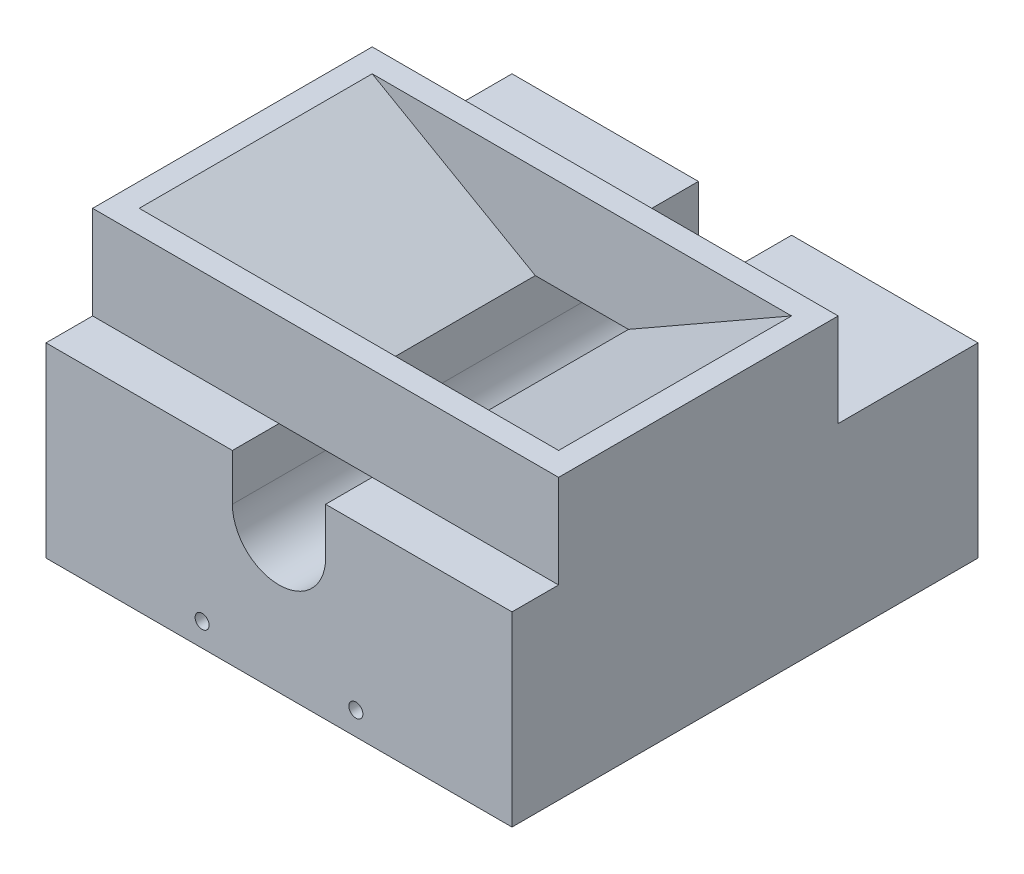
SolidWorks part; units mm, degrees
ref_plane "Front Plane" through (0, 0, 0) normal (0, 0, 1) x (1, 0, 0)
ref_plane "Top Plane" through (0, 0, 0) normal (0, 1, 0) x (1, 0, 0)
ref_plane "Right Plane" through (0, 0, 0) normal (1, 0, 0) x (0, 0, -1)
sketch "Sketch4" plane through (0, 0, 0) normal (0, 0, 1) x (1, 0, 0)
  line L1 (50, -30) -> (-50, -30)
  line L2 (50, -30) -> (50, 30)
  line L3 (50, 30) -> (-50, 30)
  line L4 (-50, -30) -> (-50, 30)
  line L5 (50, -30) -> (-50, 30) construction
  line L6 (50, 30) -> (-50, -30) construction
  point P0 (0, 0)
  dimension "D1" = 60
  dimension "D2" = 100
extrude "Boss-Extrude2" add sketch "Sketch4" along normal blind 100
sketch "Sketch6" plane through (0, 0, 100) normal (0, 0, 1) x (1, 0, 0)
  line L1 (-10, 10) -> (10, 10)
  line L2 (-10, 10) -> (-10, 0)
  line L4 (10, 10) -> (10, 0)
  line L5 (-10, 10) -> (-7.0711, 7.0711) construction
  line L7 (50, -30) -> (50, 30) construction
  arc A0 (-10, 0) -> (10, 0) centre (0, 0) ccw
  point P0 (0, 0)
  dimension "D5" = 20
  dimension "D4" = 40
extrude "Cut-Extrude1" cut sketch "Sketch6" against normal blind 100
sketch "Sketch7" plane through (50, 0, 0) normal (1, 0, 0) x (0, 0, -1)
  line L0 (-100, 30) -> (0, 30) construction
  line L1 (0, 30) -> (-30, 30)
  line L2 (0, 30) -> (0, 10)
  line L3 (0, 10) -> (-30, 10)
  line L4 (-30, 30) -> (-30, 10)
  line L5 (-100, -30) -> (-100, 30) construction
  dimension "D1" = 20
  dimension "D2" = 30
  dimension "D3" = 70
extrude "Cut-Extrude2" cut sketch "Sketch7" against normal blind 100
sketch "Sketch10" plane through (0, 30, 0) normal (0, 1, 0) x (1, 0, 0)
  line L1 (-45, -35) -> (45, -35)
  line L2 (-45, -35) -> (-45, -85)
  line L3 (-45, -85) -> (45, -85)
  line L4 (45, -35) -> (45, -85)
  line L9 (-50, -100) -> (-50, -30) construction
  line L10 (-50, -30) -> (-10, -30) construction
  dimension "D1" = 50
  dimension "D3" = 90
  dimension "D6" = 5
  dimension "D7" = 5
extrude "Cut-Extrude6" cut sketch "Sketch10" against normal blind 20
sketch "Sketch11" plane through (0, 0, 35) normal (0, 0, 1) x (1, 0, 0)
  line L0 (-45, 10) -> (-45, 30) construction
  line L2 (-45, 30) -> (-45, 10)
  line L3 (-45, 10) -> (-10, 10)
  line L5 (45, 30) -> (-45, 30) construction
  line L6 (-45, 30) -> (-10, 10)
extrude "Boss-Extrude3" add sketch "Sketch11" along normal up to next
sketch "Sketch12" plane through (0, 0, 35) normal (0, 0, 1) x (1, 0, 0)
  line L0 (10, 10) -> (45, 30)
  line L1 (10, 10) -> (45, 10)
  line L4 (45, 10) -> (45, 30)
extrude "Boss-Extrude4" add sketch "Sketch12" along normal up to next
sketch "Sketch13" plane through (0, 0, 100) normal (0, 0, 1) x (1, 0, 0)
  line L1 (-50, -30) -> (50, -30) construction
  circle A0 centre (-16.5, -25) radius 1.5
  circle A1 centre (16.5, -25) radius 1.5
  point P9 (0, 0)
  dimension "D1" = 3
  dimension "D2" = 3
  dimension "D3" = 16.5
  dimension "D4" = 16.5
  dimension "D5" = 5
  dimension "D6" = 5
extrude "Cut-Extrude7" cut sketch "Sketch13" against normal blind 40
sketch "Sketch14" plane through (0, -30, 0) normal (0, -1, 0) x (1, 0, 0)
  line L9 (-50, 100) -> (50, 100) construction
  line L10 (-26.5, 95) -> (-6.5, 95)
  line L11 (-26.5, 95) -> (-26.5, 55)
  line L12 (-26.5, 55) -> (-6.5, 55)
  line L13 (-6.5, 95) -> (-6.5, 55)
  line L14 (6.5, 95) -> (26.5, 95)
  line L15 (6.5, 95) -> (6.5, 55)
  line L16 (6.5, 55) -> (26.5, 55)
  line L17 (26.5, 95) -> (26.5, 55)
  line L18 (-50, 100) -> (-50, 0) construction
  line L19 (50, 100) -> (50, 0) construction
  dimension "D1" = 5
  dimension "D2" = 5
  dimension "D3" = 40
  dimension "D4" = 40
  dimension "D5" = 20
  dimension "D6" = 20
  dimension "D7" = 23.5
  dimension "D8" = 23.5
extrude "Cut-Extrude8" cut sketch "Sketch14" against normal blind 10
sketch "Sketch15" plane through (0, 0, 0) normal (0, 0, -1) x (-1, 0, 0)
  line L1 (50, -30) -> (-50, -30) construction
  line L3 (-50, -30) -> (-50, 10) construction
  circle A0 centre (-25, -25) radius 1.5
  circle A1 centre (25, -25) radius 1.5
  dimension "D1" = 3
  dimension "D2" = 3
  dimension "D3" = 5
  dimension "D4" = 5
  dimension "D5" = 50
  dimension "D6" = 25
extrude "Cut-Extrude9" cut sketch "Sketch15" against normal blind 40
sketch "Sketch16" plane through (0, -30, 0) normal (0, -1, 0) x (-1, 0, 0)
  line L0 (50, 0) -> (-50, 0) construction
  line L1 (-35, -5) -> (-15, -5)
  line L2 (-35, -5) -> (-35, -45)
  line L3 (-35, -45) -> (-15, -45)
  line L4 (-15, -5) -> (-15, -45)
  line L5 (15, -5) -> (35, -5)
  line L6 (15, -5) -> (15, -45)
  line L7 (15, -45) -> (35, -45)
  line L8 (35, -5) -> (35, -45)
  line L9 (-50, -100) -> (-50, 0) construction
  line L10 (50, -100) -> (50, 0) construction
  dimension "D1" = 40
  dimension "D2" = 5
  dimension "D3" = 5
  dimension "D4" = 40
  dimension "D5" = 20
  dimension "D6" = 20
  dimension "D7" = 15
  dimension "D8" = 15
extrude "Cut-Extrude10" cut sketch "Sketch16" against normal blind 10
sketch "Sketch17" plane through (50, 0, 0) normal (1, 0, 0) x (0, 0, -1)
  line L1 (-100, 30) -> (-90, 30)
  line L2 (-100, 30) -> (-100, 10)
  line L3 (-100, 10) -> (-90, 10)
  line L4 (-90, 30) -> (-90, 10)
  dimension "D1" = 10
  dimension "D2" = 20
extrude "Cut-Extrude11" cut sketch "Sketch17" against normal through all
